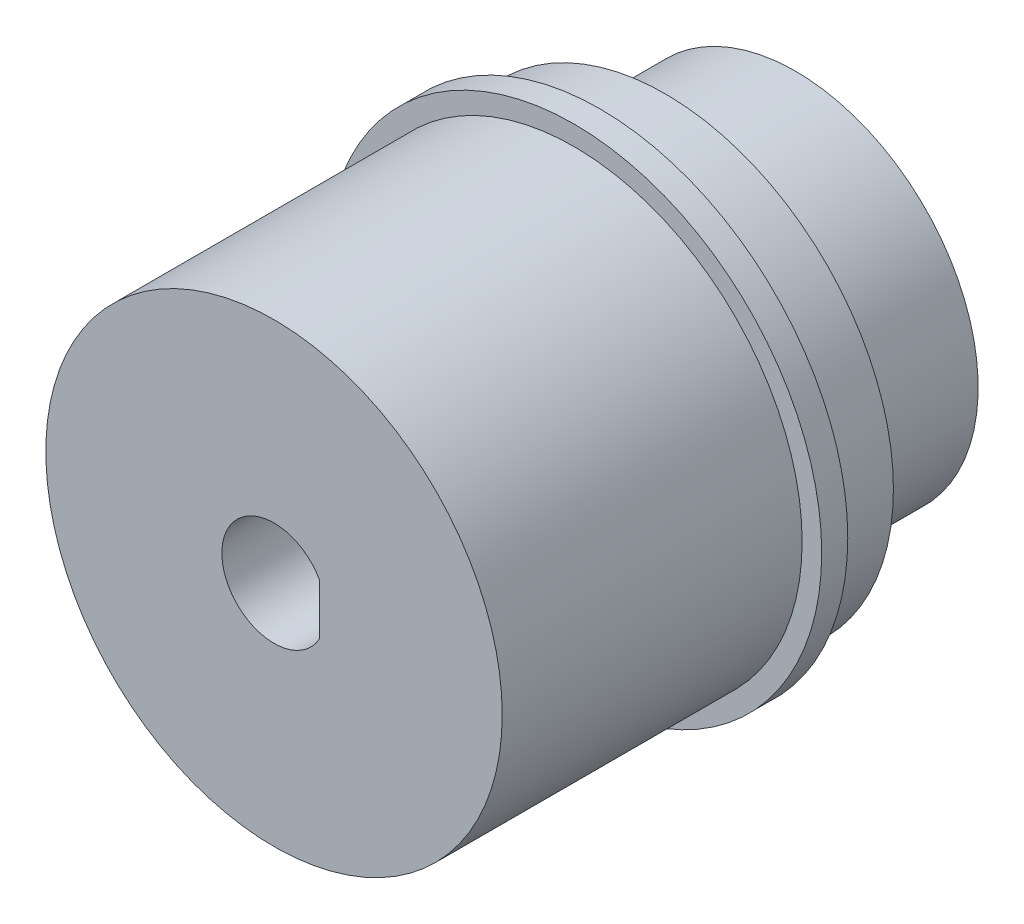
SolidWorks part; units mm, degrees
ref_plane "Front Plane" through (0, 0, 0) normal (0, 0, 1) x (1, 0, 0)
ref_plane "Top Plane" through (0, 0, 0) normal (0, 1, 0) x (1, 0, 0)
ref_plane "Right Plane" through (0, 0, 0) normal (1, 0, 0) x (0, 0, -1)
sketch "Sketch1" plane through (0, 0, 0) normal (0, 0, 1) x (1, 0, 0)
  circle A0 centre (0, 0) radius 14
  dimension "D1" = 28
extrude "Boss-Extrude2" add sketch "Sketch1" along normal blind 10
sketch "Sketch2" plane through (0, 0, 10) normal (0, 0, 1) x (1, 0, 0)
  circle A0 centre (0, 0) radius 17.5
  dimension "D1" = 35
extrude "Boss-Extrude3" add sketch "Sketch2" along normal blind 5
sketch "Sketch3" plane through (0, 0, 15) normal (0, 0, 1) x (1, 0, 0)
  circle A0 centre (0, 0) radius 19
extrude "Boss-Extrude4" add sketch "Sketch3" along normal blind 2
sketch "Sketch4" plane through (0, 0, 17) normal (0, 0, 1) x (1, 0, 0)
  circle A0 centre (0, 0) radius 17.5
extrude "Boss-Extrude5" add sketch "Sketch4" along normal blind 23
sketch "Sketch5" plane through (0, 0, 0) normal (0, 0, -1) x (-1, 0, 0)
  line L0 (0, 0) -> (10, 0) construction
  line L1 (10, 0) -> (10, -9.798)
  line L2 (10, 0) -> (10, 9.798)
  circle A0 centre (0, 0) radius 14 construction
  circle A1 centre (0, 0) radius 14 construction
  arc A2 (10, 9.798) -> (10, -9.798) centre (0, 0) cw
  circle M2 centre (0, 0) radius 14
  dimension "D1" = 10
extrude "Cut-Extrude1" cut sketch "Sketch5" against normal blind 10 contours L2 L1 M2
sketch "Sketch10" plane through (0, 0, 0) normal (0, 0, -1) x (-1, 0, 0)
  line L0 (0, 0) -> (-14, 0) construction
  arc A0 (10, 9.798) -> (10, -9.798) centre (0, 0) ccw construction
  circle A1 centre (0, 0) radius 2.75
  dimension "D1" = 5.5
extrude "Cut-Extrude2" cut sketch "Sketch10" against normal blind 15
sketch "Sketch12" plane through (0, 0, 40) normal (0, 0, 1) x (1, 0, 0)
  line L0 (0, 0) -> (3.5, 0) construction
  line L1 (3.5, 0) -> (3.5, -1.9365)
  line L2 (3.5, 0) -> (3.5, 1.9365)
  arc A0 (3.5, 1.9365) -> (3.5, -1.9365) centre (0, 0) ccw
  dimension "D1" = 3.5
extrude "Cut-Extrude3" cut sketch "Sketch12" against normal blind 15
